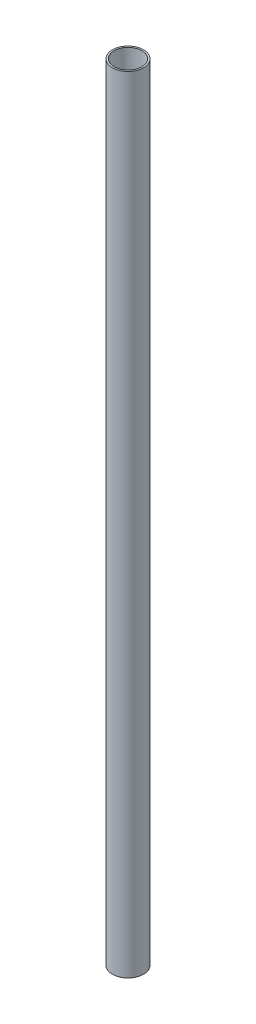
SolidWorks part; units mm, degrees
ref_plane "Front Plane" through (0, 0, 0) normal (0, 0, 1) x (1, 0, 0)
ref_plane "Top Plane" through (0, 0, 0) normal (0, 1, 0) x (1, 0, 0)
ref_plane "Right Plane" through (0, 0, 0) normal (1, 0, 0) x (0, 0, -1)
sketch "Sketch1" plane through (0, 0, 0) normal (0, 1, 0) x (1, 0, 0)
  circle A0 centre (0, 0) radius 30.226
  circle A1 centre (0, 0) radius 27.051
  dimension "D1" = 60.452
  dimension "D2" = 3.175
extrude "Boss-Extrude1" add sketch "Sketch1" along normal blind 1524
